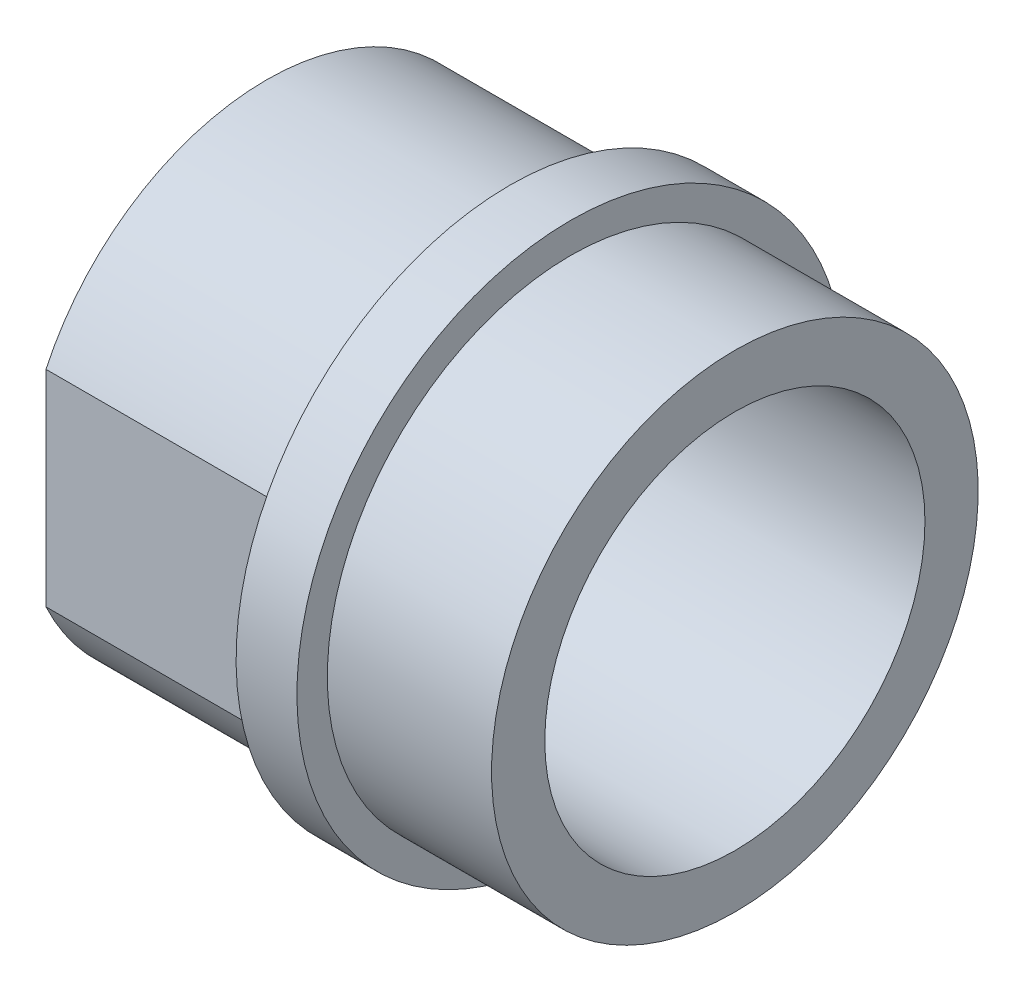
SolidWorks part; units mm, degrees
ref_plane "前视基准面" through (0, 0, 0) normal (0, 0, 1) x (1, 0, 0)
ref_plane "上视基准面" through (0, 0, 0) normal (0, 1, 0) x (1, 0, 0)
ref_plane "右视基准面" through (0, 0, 0) normal (1, 0, 0) x (0, 0, -1)
sketch "草图3" plane through (0, 0, 0) normal (0, 0, 1) x (1, 0, 0)
  line L0 (0, 0) -> (0, 8)
  line L5 (0, 8) -> (8, 8)
  line L6 (8, 8) -> (8, 9)
  line L7 (8, 9) -> (10, 9)
  line L8 (10, 9) -> (10, 8)
  line L9 (10, 8) -> (15.4, 8)
  line L10 (15.4, 8) -> (15.4, 0)
  line L11 (15.4, 0) -> (0, 0)
  dimension "D1" = 8
  dimension "D2" = 9
  dimension "D3" = 8
  dimension "D4" = 7.4
  dimension "D5" = 2
revolve "旋转1" add sketch "草图3" angle 360 about L11
sketch "草图4" plane through (15.4, 0, 0) normal (-1, 0, 0) x (0, 0, 1)
  circle A0 centre (0, 0) radius 6.25
  dimension "D1" = 12.5
extrude "切除-拉伸1" cut sketch "草图4" along normal blind 10
sketch "草图5" plane through (0, 0, 0) normal (-1, 0, 0) x (0, 0, 1)
  line L0 (0, 11.3906) -> (0, -13.4422) construction
  line L1 (7.25, 9.4245) -> (7.25, -10.4503)
  line L2 (-12.1225, 9.4245) -> (-7.25, 9.4245)
  line L3 (-12.1225, 9.4245) -> (-12.1225, -10.4503)
  line L4 (-12.1225, -10.4503) -> (-7.25, -10.4503)
  line L5 (-7.25, 9.4245) -> (-7.25, -10.4503)
  line L6 (12.1225, -10.4503) -> (7.25, -10.4503)
  line L7 (12.1225, 9.4245) -> (12.1225, -10.4503)
  line L8 (12.1225, 9.4245) -> (7.25, 9.4245)
  dimension "D1" = 14.5
extrude "切除-拉伸2" cut sketch "草图5" against normal up to surface (8 mm away) up to face at (8, 8, 0)
